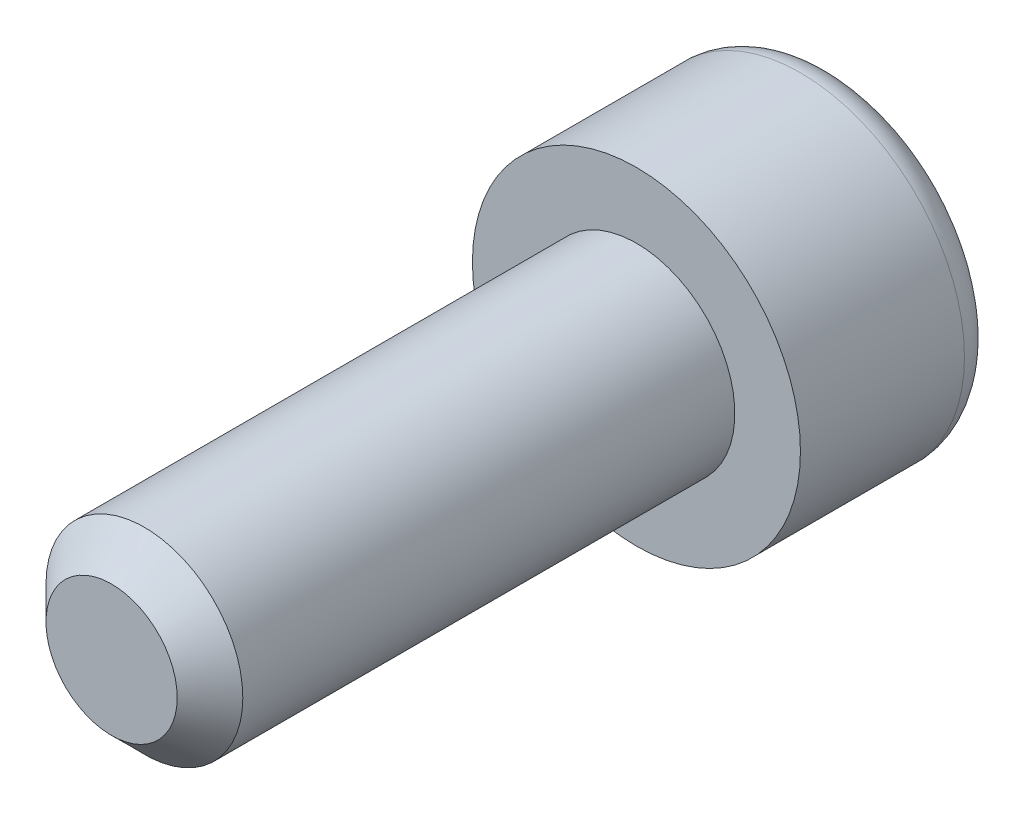
SolidWorks part; units mm, degrees
ref_plane "Face" through (0, 0, 0) normal (0, 0, 1) x (1, 0, 0)
ref_plane "Dessus" through (0, 0, 0) normal (0, 1, 0) x (1, 0, 0)
ref_plane "Droite" through (0, 0, 0) normal (1, 0, 0) x (0, 0, -1)
sketch "Esquisse1" plane through (0, 0, 0) normal (0, 0, 1) x (1, 0, 0)
  circle A0 centre (0, 0) radius 1.5
  dimension "D1" = 3
extrude "Base-Extrusion" add sketch "Esquisse1" along normal blind 8
chamfer "Chanfrein1" distance 0.5 angle 45 1 edges at (1.5, 0, 8)
sketch "Esquisse2" plane through (0, 0, 0) normal (0, 0, -1) x (-1, 0, 0)
  circle A0 centre (0, 0) radius 2.5
  dimension "D1" = 5
extrude "Boss.-Extru.1" add sketch "Esquisse2" along normal blind 3
fillet "Congé1" radius 0.5 1 edges at (-2.5, 0, -3)
sketch "Esquisse3" plane through (0, 0, -3) normal (0, 0, -1) x (-1, 0, 0)
  line L1 (1.7321, 0) -> (0.866, 1.5)
  line L2 (0.866, 1.5) -> (-0.866, 1.5)
  line L3 (-0.866, 1.5) -> (-1.7321, 0)
  line L4 (-1.7321, 0) -> (-0.866, -1.5)
  line L5 (-0.866, -1.5) -> (0.866, -1.5)
  line L6 (0.866, -1.5) -> (1.7321, 0)
  circle A0 centre (0, 0) radius 1.5 construction
  dimension "D1" = 3
extrude "Enlèv. mat.-Extru.1" cut sketch "Esquisse3" against normal blind 2.5
